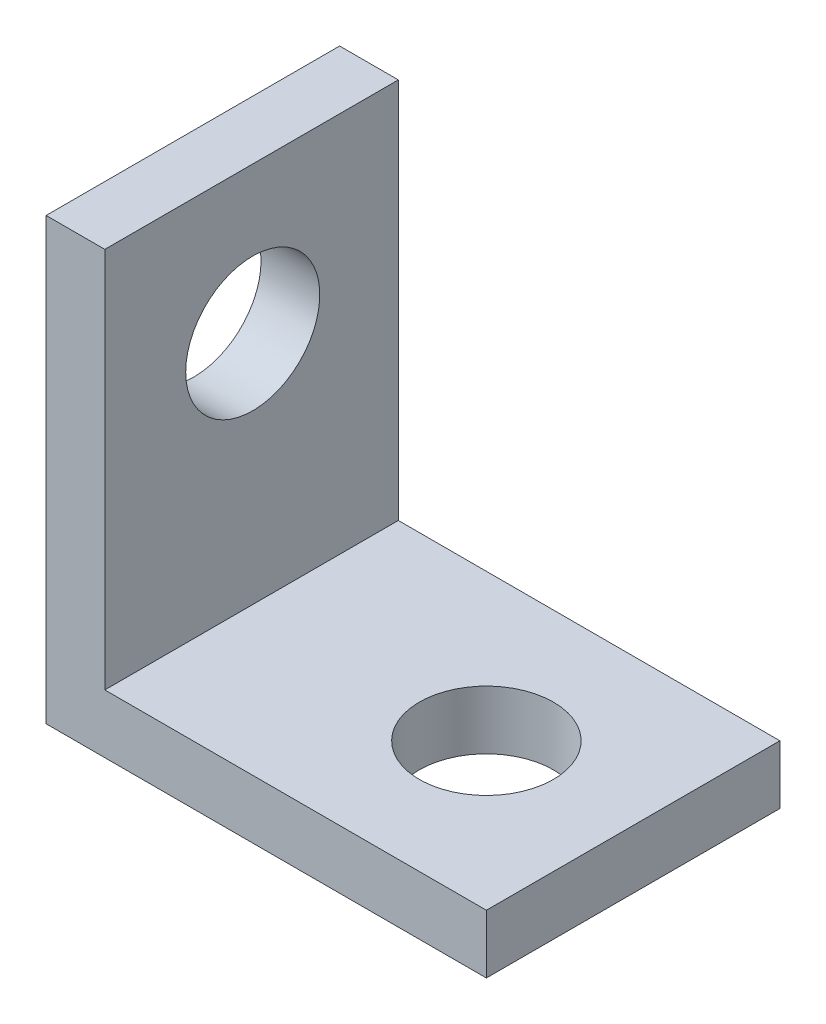
SolidWorks part; units mm, degrees
ref_plane "Front Plane" through (0, 0, 0) normal (0, 0, 1) x (1, 0, 0)
ref_plane "Top Plane" through (0, 0, 0) normal (0, 1, 0) x (1, 0, 0)
ref_plane "Right Plane" through (0, 0, 0) normal (1, 0, 0) x (0, 0, -1)
sketch "Sketch1" plane through (0, 0, 0) normal (0, 0, 1) x (1, 0, 0)
  line L0 (0, 0) -> (0, 19.05)
  line L1 (0, 0) -> (19.05, 0)
  line L2 (2.54, 2.54) -> (19.05, 2.54)
  line L3 (2.54, 2.54) -> (2.54, 19.05)
  line L4 (0, 19.05) -> (2.54, 19.05)
  line L5 (19.05, 0) -> (19.05, 2.54)
  dimension "D1" = 19.05
  dimension "D2" = 2.54
  dimension ".5in" = 19.05
extrude "Boss-Extrude1" add sketch "Sketch1" along normal blind 12.7
sketch "Sketch2" plane through (0, 0, 0) normal (1, 0, 0) x (0, 0, -1)
  line L0 (-6.2999, 19.05) -> (-6.2999, 0) construction
  line L1 (-12.7, 19.05) -> (0, 19.05) construction
  line L2 (-12.7, 0) -> (0, 0) construction
  circle A0 centre (-6.2999, 12.7) radius 2.9
  point P8 (0, 0)
  dimension "D1" = 5.8
  dimension "D2" = 12.7
extrude "Cut-Extrude1" cut sketch "Sketch2" along normal blind 12.7
sketch "Sketch3" plane through (0, 0, 0) normal (0, 1, 0) x (1, 0, 0)
  line L0 (19.05, -6.35) -> (0, -6.35) construction
  line L1 (19.05, -12.7) -> (19.05, 0) construction
  line L2 (0, -12.7) -> (0, 0) construction
  circle A0 centre (12.7, -6.35) radius 2.9
  dimension "D1" = 5.8
  dimension "D2" = 12.7
extrude "Cut-Extrude3" cut sketch "Sketch3" along normal blind 12.7
